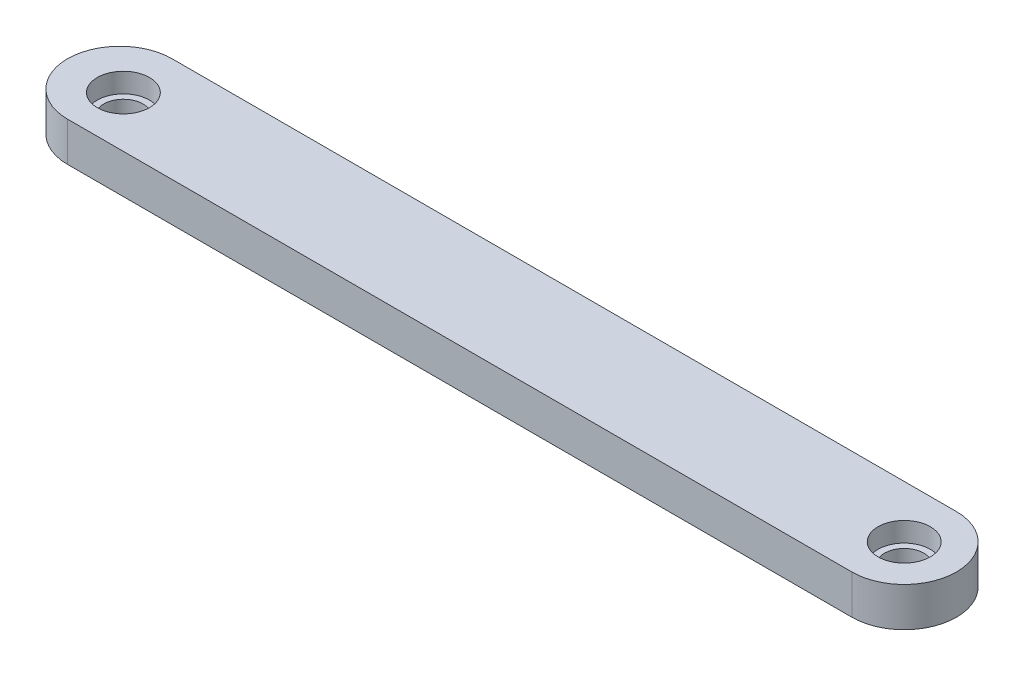
SolidWorks part; units mm, degrees
ref_plane "Front Plane" through (0, 0, 0) normal (0, 0, 1) x (1, 0, 0)
ref_plane "Top Plane" through (0, 0, 0) normal (0, 1, 0) x (1, 0, 0)
ref_plane "Right Plane" through (0, 0, 0) normal (1, 0, 0) x (0, 0, -1)
sketch "Sketch1" plane through (0, 0, 0) normal (0, 1, 0) x (1, 0, 0)
  line L0 (-56.2508, 0) -> (60, 0) construction
  line L1 (-60, -8) -> (60, -8)
  line L3 (-60, 8) -> (60, 8)
  line L11 (0, 8) -> (0, -8) construction
  circle A2 centre (-59.2433, -0.2116) radius 3
  circle A3 centre (60, 0) radius 3
  arc A5 (-60, 8) -> (-60, -8) centre (-60, 0) ccw
  arc A7 (60, -8) -> (60, 8) centre (60, 0) ccw
  point P0 (0, 0)
  point P17 (0, 0)
  dimension "D3" = 6
  dimension "D4" = 6
  dimension "D8" = 16
  dimension "D1" = 120
  dimension "D2" = 8
  dimension "D6" = 60
extrude "Boss-Extrude1" add sketch "Sketch1" along normal blind 6
sketch "Sketch3" plane through (0, 6, 0) normal (0, 1, 0) x (1, 0, 0)
  circle A0 centre (-59.2433, -0.2116) radius 4
  circle A2 centre (60, 0) radius 4
  dimension "D1" = 8
  dimension "D3" = 8
extrude "Cut-Extrude1" cut sketch "Sketch3" against normal blind 3
